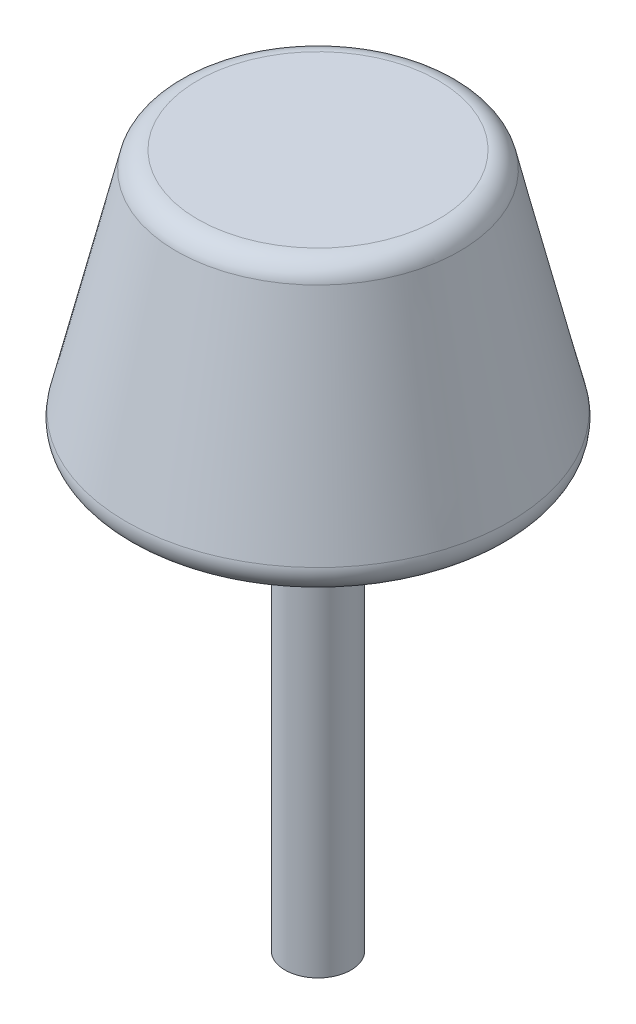
SolidWorks part; units mm, degrees
material "聚脂树脂"
ref_plane "前视基准面" through (0, 0, 0) normal (0, 0, 1) x (1, 0, 0)
ref_plane "上视基准面" through (0, 0, 0) normal (0, 1, 0) x (1, 0, 0)
ref_plane "右视基准面" through (0, 0, 0) normal (1, 0, 0) x (0, 0, -1)
sketch "草图2" plane through (0, 0, 0) normal (0, 0, 1) x (1, 0, 0)
  line L0 (3, 0) -> (18, 0)
  line L1 (0, 0) -> (0, 23)
  line L2 (0, 23) -> (12.5, 23)
  line L3 (12.5, 23) -> (18, 0)
  line L4 (3, 0) -> (3, -40)
  line L5 (3, -40) -> (0, -40)
  line L6 (0, -40) -> (0, 0)
revolve "旋转1" add sketch "草图2" angle 360 about L1
fillet "圆角1" radius 2 2 edges at (0, 0, -18) (0, 23, -12.5)
